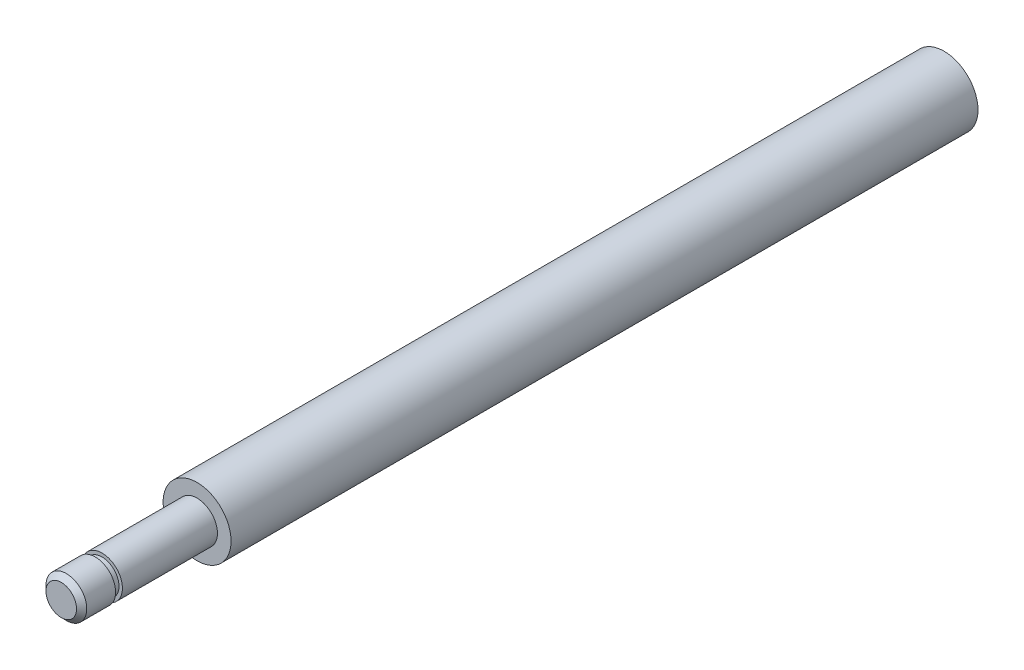
SolidWorks part; units mm, degrees
material "Q235A"
ref_plane "前视" through (0, 0, 0) normal (0, 0, 1) x (1, 0, 0)
ref_plane "上视" through (0, 0, 0) normal (0, 1, 0) x (1, 0, 0)
ref_plane "右视" through (0, 0, 0) normal (1, 0, 0) x (0, 0, -1)
sketch "草图1" plane through (0, 0, 0) normal (0, 0, 1) x (1, 0, 0)
  circle A0 centre (0, 0) radius 10
  dimension "D1" = 20
extrude "凸台-拉伸1" add sketch "草图1" along normal blind 260
sketch "草图2" plane through (0, 0, 260) normal (0, 0, 1) x (1, 0, 0)
  circle A0 centre (0, 0) radius 6
  dimension "D1" = 12
extrude "切除-拉伸1" cut sketch "草图2" against normal blind 40 flip side to cut
cosmetic thread "装饰螺纹线1" parameters "D2"=10.2
ref_plane "基准面1" through (0, 0, 250) normal (0, 0, 1) x (1, 0, 0)
sketch "草图3" plane through (0, 0, 250) normal (0, 0, 1) x (1, 0, 0)
  circle A0 centre (0, 0) radius 5
  dimension "D1" = 10
extrude "切除-拉伸2" cut sketch "草图3" against normal blind 2 flip side to cut
chamfer "倒角1" distance 1.5 angle 45 1 edges at (6, 0, 260)
